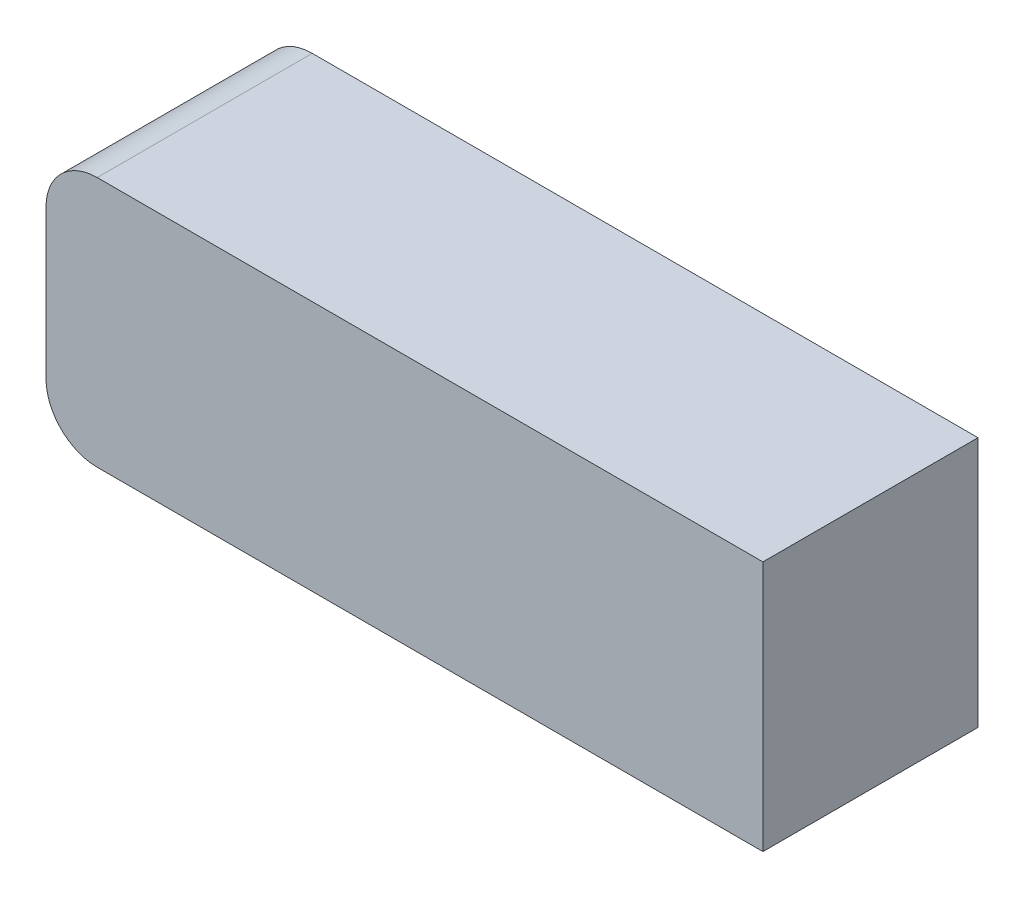
SolidWorks part; units mm, degrees
ref_plane "Alzado" through (0, 0, 0) normal (0, 0, 1) x (1, 0, 0)
ref_plane "Planta" through (0, 0, 0) normal (0, 1, 0) x (1, 0, 0)
ref_plane "Vista lateral" through (0, 0, 0) normal (1, 0, 0) x (0, 0, -1)
sketch "Croquis2" plane through (0, 0, 0) normal (0, 1, 0) x (1, 0, 0)
  line L1 (70, -21) -> (-70, -21)
  line L2 (70, -21) -> (70, 21)
  line L3 (70, 21) -> (-70, 21)
  line L4 (-70, -21) -> (-70, 21)
  line L5 (70, -21) -> (-70, 21) construction
  line L6 (70, 21) -> (-70, -21) construction
  point P0 (0, 0)
  dimension "D1" = 140
  dimension "D2" = 42
extrude "Saliente-Extruir1" add sketch "Croquis2" along normal mid plane 49
fillet "Redondeo1" radius 10 2 edges at (-70, -24.5, 0) (-70, 24.5, 0)
